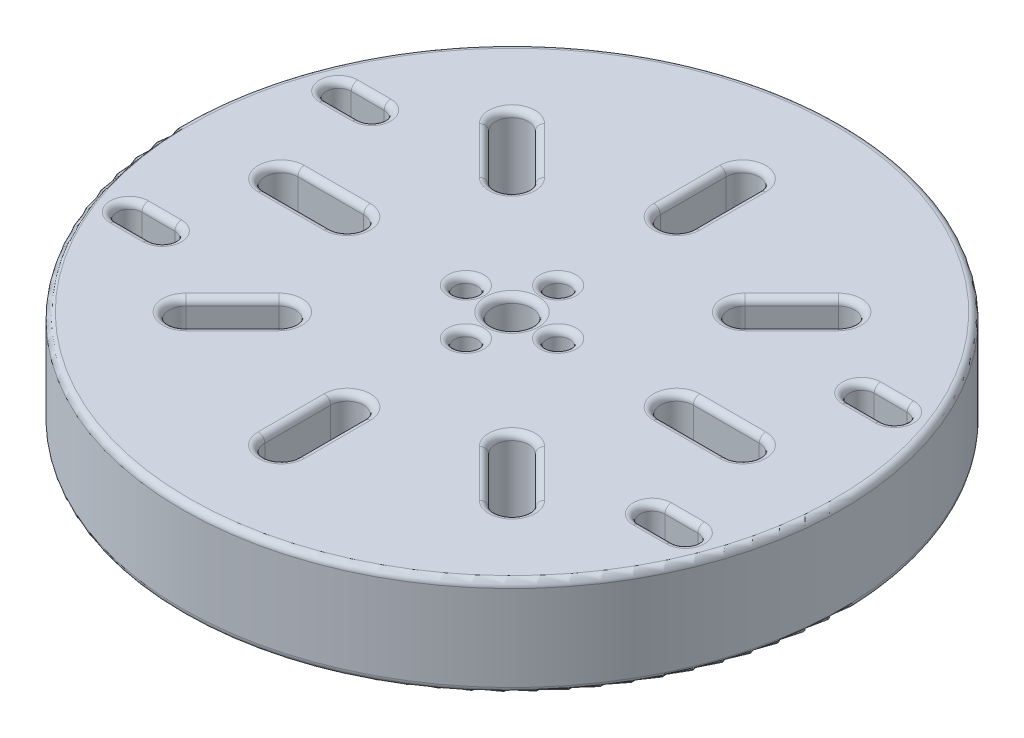
SolidWorks part; units mm, degrees
ref_plane "Front" through (0, 0, 0) normal (0, 0, 1) x (1, 0, 0)
ref_plane "Top" through (0, 0, 0) normal (0, 1, 0) x (1, 0, 0)
ref_plane "Right" through (0, 0, 0) normal (1, 0, 0) x (0, 0, -1)
sketch "Sketch1" plane through (0, 0, 0) normal (0, 1, 0) x (1, 0, 0)
  circle A0 centre (0, 0) radius 50
  dimension "D1" = 100
extrude "Boss-Extrude1" add sketch "Sketch1" along normal blind 15
sketch "Sketch5" plane through (0, 0, 0) normal (0, -1, 0) x (1, 0, 0)
  line L0 (25, 0) -> (35, 0) construction
  line L1 (25, 2.5) -> (35, 2.5)
  line L2 (25, -2.5) -> (35, -2.5)
  line L3 (17.6777, -17.6777) -> (24.7487, -24.7487) construction
  line L4 (19.4454, -15.9099) -> (26.5165, -22.981)
  line L5 (15.9099, -19.4454) -> (22.981, -26.5165)
  line L6 (0, -25) -> (0, -35) construction
  line L7 (2.5, -25) -> (2.5, -35)
  line L8 (-2.5, -25) -> (-2.5, -35)
  line L9 (-17.6777, -17.6777) -> (-24.7487, -24.7487) construction
  line L10 (-15.9099, -19.4454) -> (-22.981, -26.5165)
  line L11 (-19.4454, -15.9099) -> (-26.5165, -22.981)
  line L12 (37.17, -15.88) -> (42.17, -15.88) construction
  line L13 (37.17, -13.98) -> (42.17, -13.98)
  line L14 (37.17, -17.78) -> (42.17, -17.78)
  line L15 (37.17, 15.88) -> (42.17, 15.88) construction
  line L16 (37.17, 17.78) -> (42.17, 17.78)
  line L17 (37.17, 13.98) -> (42.17, 13.98)
  line L18 (-42.17, -15.88) -> (-37.17, -15.88) construction
  line L19 (-42.17, -13.98) -> (-37.17, -13.98)
  line L20 (-42.17, -17.78) -> (-37.17, -17.78)
  line L21 (-42.17, 15.88) -> (-37.17, 15.88) construction
  line L22 (-42.17, 17.78) -> (-37.17, 17.78)
  line L23 (-42.17, 13.98) -> (-37.17, 13.98)
  line L24 (-25, 0) -> (-35, 0) construction
  line L25 (-25, -2.5) -> (-35, -2.5)
  line L26 (-25, 2.5) -> (-35, 2.5)
  line L27 (-17.6777, 17.6777) -> (-24.7487, 24.7487) construction
  line L28 (-19.4454, 15.9099) -> (-26.5165, 22.981)
  line L29 (-15.9099, 19.4454) -> (-22.981, 26.5165)
  line L30 (0, 25) -> (0, 35) construction
  line L31 (-2.5, 25) -> (-2.5, 35)
  line L32 (2.5, 25) -> (2.5, 35)
  line L33 (17.6777, 17.6777) -> (24.7487, 24.7487) construction
  line L34 (15.9099, 19.4454) -> (22.981, 26.5165)
  line L35 (19.4454, 15.9099) -> (26.5165, 22.981)
  arc A0 (25, 2.5) -> (25, -2.5) centre (25, 0) ccw
  arc A1 (35, -2.5) -> (35, 2.5) centre (35, 0) ccw
  arc A2 (19.4454, -15.9099) -> (15.9099, -19.4454) centre (17.6777, -17.6777) ccw
  arc A3 (22.981, -26.5165) -> (26.5165, -22.981) centre (24.7487, -24.7487) ccw
  arc A4 (2.5, -25) -> (-2.5, -25) centre (0, -25) ccw
  arc A5 (-2.5, -35) -> (2.5, -35) centre (0, -35) ccw
  arc A6 (-15.9099, -19.4454) -> (-19.4454, -15.9099) centre (-17.6777, -17.6777) ccw
  arc A7 (-26.5165, -22.981) -> (-22.981, -26.5165) centre (-24.7487, -24.7487) ccw
  arc A8 (37.17, -13.98) -> (37.17, -17.78) centre (37.17, -15.88) ccw
  arc A9 (42.17, -17.78) -> (42.17, -13.98) centre (42.17, -15.88) ccw
  arc A10 (37.17, 17.78) -> (37.17, 13.98) centre (37.17, 15.88) ccw
  arc A11 (42.17, 13.98) -> (42.17, 17.78) centre (42.17, 15.88) ccw
  arc A12 (-42.17, -13.98) -> (-42.17, -17.78) centre (-42.17, -15.88) ccw
  arc A13 (-37.17, -17.78) -> (-37.17, -13.98) centre (-37.17, -15.88) ccw
  arc A14 (-42.17, 17.78) -> (-42.17, 13.98) centre (-42.17, 15.88) ccw
  arc A15 (-37.17, 13.98) -> (-37.17, 17.78) centre (-37.17, 15.88) ccw
  arc A16 (-25, -2.5) -> (-25, 2.5) centre (-25, 0) ccw
  arc A17 (-35, 2.5) -> (-35, -2.5) centre (-35, 0) ccw
  arc A18 (-19.4454, 15.9099) -> (-15.9099, 19.4454) centre (-17.6777, 17.6777) ccw
  arc A19 (-22.981, 26.5165) -> (-26.5165, 22.981) centre (-24.7487, 24.7487) ccw
  arc A20 (-2.5, 25) -> (2.5, 25) centre (0, 25) ccw
  arc A21 (2.5, 35) -> (-2.5, 35) centre (0, 35) ccw
  arc A22 (15.9099, 19.4454) -> (19.4454, 15.9099) centre (17.6777, 17.6777) ccw
  arc A23 (26.5165, 22.981) -> (22.981, 26.5165) centre (24.7487, 24.7487) ccw
  point P2 (30, 0)
  point P12 (21.2132, -21.2132)
  point P19 (0, -30)
  point P26 (-21.2132, -21.2132)
  point P31 (0, 0)
  point P32 (39.67, -15.88)
  point P40 (39.67, 15.88)
  point P47 (-39.67, -15.88)
  point P54 (-39.67, 15.88)
  point P62 (-30, 0)
  point P69 (-21.2132, 21.2132)
  point P76 (0, 30)
  point P83 (21.2132, 21.2132)
  dimension "D7" = 5
  dimension "D8" = 39.67
  dimension "D1" = 5
  dimension "D2" = 10
  dimension "D3" = 30
  dimension "D5" = 3.8
  dimension "D6" = 15.88
  dimension "D9" = 2
  dimension "D10" = 2
  dimension "D4" = 8
extrude "Cut-Extrude1" cut sketch "Sketch5" against normal through all
sketch "Sketch6" plane through (0, 0, 0) normal (0, -1, 0) x (1, 0, 0)
  circle A0 centre (0, 0) radius 12.5
  dimension "D1" = 25
extrude "Cut-Extrude2" cut sketch "Sketch6" against normal blind 5
sketch "Sketch7" plane through (0, 5, 0) normal (0, -1, 0) x (1, 0, 0)
  circle A0 centre (7, 0) radius 1.75
  circle A1 centre (0, -7) radius 1.75
  circle A2 centre (-7, 0) radius 1.75
  circle A3 centre (0, 7) radius 1.75
  circle A4 centre (0, 0) radius 3
  point P11 (0, 0)
  dimension "D1" = 3.5
  dimension "D4" = 6
  dimension "D2" = 7
  dimension "D3" = 4
extrude "Cut-Extrude3" cut sketch "Sketch7" against normal through all
fillet "Fillet19" radius 1 104 edges at (37.5, 0, 0) (30, 0, 2.5) (22.5, 0, 0) (30, 0, -2.5) (26.5165, 0, -26.5165) (22.981, 0, -19.4454) (15.9099, 0, -15.9099) (19.4454, 0, -22.981) (0, 0, -37.5) (2.5, 0, -30) (0, 0, -22.5) (-2.5, 0, -30) (-26.5165, 0, -26.5165) (-19.4454, 0, -22.981) (-15.9099, 0, -15.9099) (-22.981, 0, -19.4454) (44.07, 0, -15.88) (39.67, 0, -13.98) (35.27, 0, -15.88) (39.67, 0, -17.78) (44.07, 0, 15.88) (39.67, 0, 17.78) (35.27, 0, 15.88) (39.67, 0, 13.98) (-35.27, 0, -15.88) (-39.67, 0, -13.98) (-44.07, 0, -15.88) (-39.67, 0, -17.78) (-35.27, 0, 15.88) (-39.67, 0, 17.78) (-44.07, 0, 15.88) (-39.67, 0, 13.98) (0, 0, -12.5) (0, 0, 50) (0, 15, 50) (30, 15, 2.5) (37.5, 15, 0) (30, 15, -2.5) (22.5, 15, 0) (22.981, 15, -19.4454) (26.5165, 15, -26.5165) (19.4454, 15, -22.981) (15.9099, 15, -15.9099) (2.5, 15, -30) (0, 15, -37.5) (-2.5, 15, -30) (0, 15, -22.5) (-19.4454, 15, -22.981) (-26.5165, 15, -26.5165) (-22.981, 15, -19.4454) (-15.9099, 15, -15.9099) (39.67, 15, -13.98) (44.07, 15, -15.88) (39.67, 15, -17.78) (35.27, 15, -15.88) (39.67, 15, 17.78) (44.07, 15, 15.88) (39.67, 15, 13.98) (35.27, 15, 15.88) (-39.67, 15, -13.98) (-35.27, 15, -15.88) (-39.67, 15, -17.78) (-44.07, 15, -15.88) (-39.67, 15, 17.78) (-35.27, 15, 15.88) (-39.67, 15, 13.98) (-44.07, 15, 15.88) (7, 15, -1.75) (0, 15, -3) (0, 15, -8.75) (-7, 15, -1.75) (0, 15, 5.25) (-30, 15, -2.5) (-37.5, 15, 0) (-30, 15, 2.5) (-22.5, 15, 0) (-22.981, 15, 19.4454) (-26.5165, 15, 26.5165) (-19.4454, 15, 22.981) (-15.9099, 15, 15.9099) (-2.5, 15, 30) (0, 15, 37.5) (2.5, 15, 30) (0, 15, 22.5) (19.4454, 15, 22.981) (26.5165, 15, 26.5165) (22.981, 15, 19.4454) (15.9099, 15, 15.9099) (-37.5, 0, 0) (-30, 0, -2.5) (-22.5, 0, 0) (-30, 0, 2.5) (-26.5165, 0, 26.5165) (-22.981, 0, 19.4454) (-15.9099, 0, 15.9099) (-19.4454, 0, 22.981) (0, 0, 37.5) (-2.5, 0, 30) (0, 0, 22.5) (2.5, 0, 30) (26.5165, 0, 26.5165) (19.4454, 0, 22.981) (15.9099, 0, 15.9099) (22.981, 0, 19.4454)
